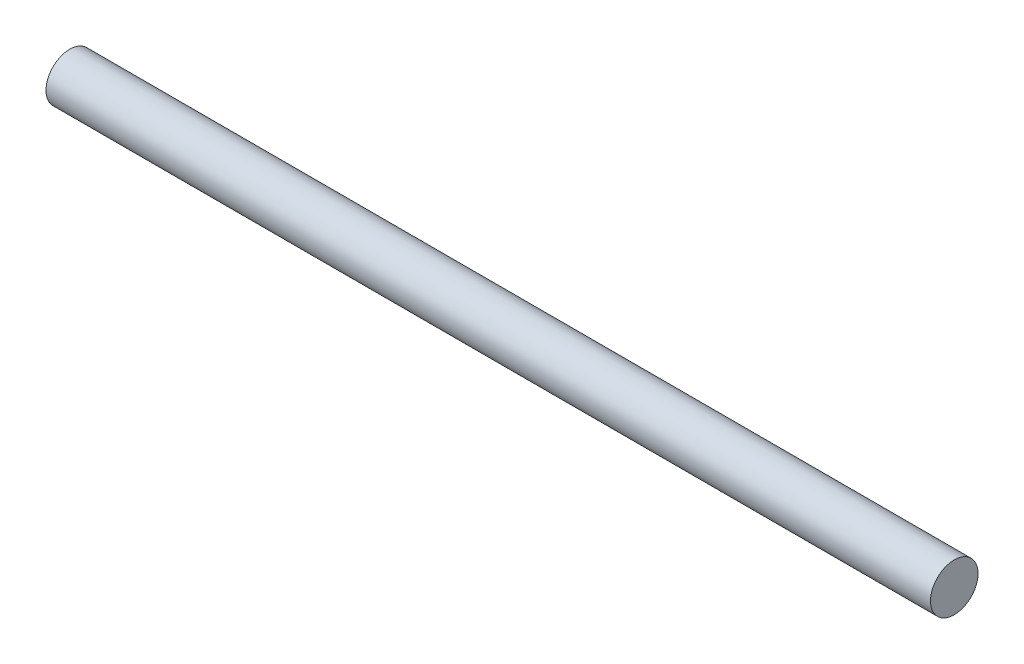
SolidWorks part; units mm, degrees
material "6061 Alloy"
ref_plane "Front Plane" through (0, 0, 0) normal (0, 0, 1) x (1, 0, 0)
ref_plane "Top Plane" through (0, 0, 0) normal (0, 1, 0) x (1, 0, 0)
ref_plane "Right Plane" through (0, 0, 0) normal (1, 0, 0) x (0, 0, -1)
sketch "Sketch1" plane through (0, 0, 0) normal (1, 0, 0) x (0, 0, -1)
  circle A0 centre (0, 0) radius 2.5
  dimension "D1" = 5
extrude "Boss-Extrude1" add sketch "Sketch1" along normal mid plane 93
